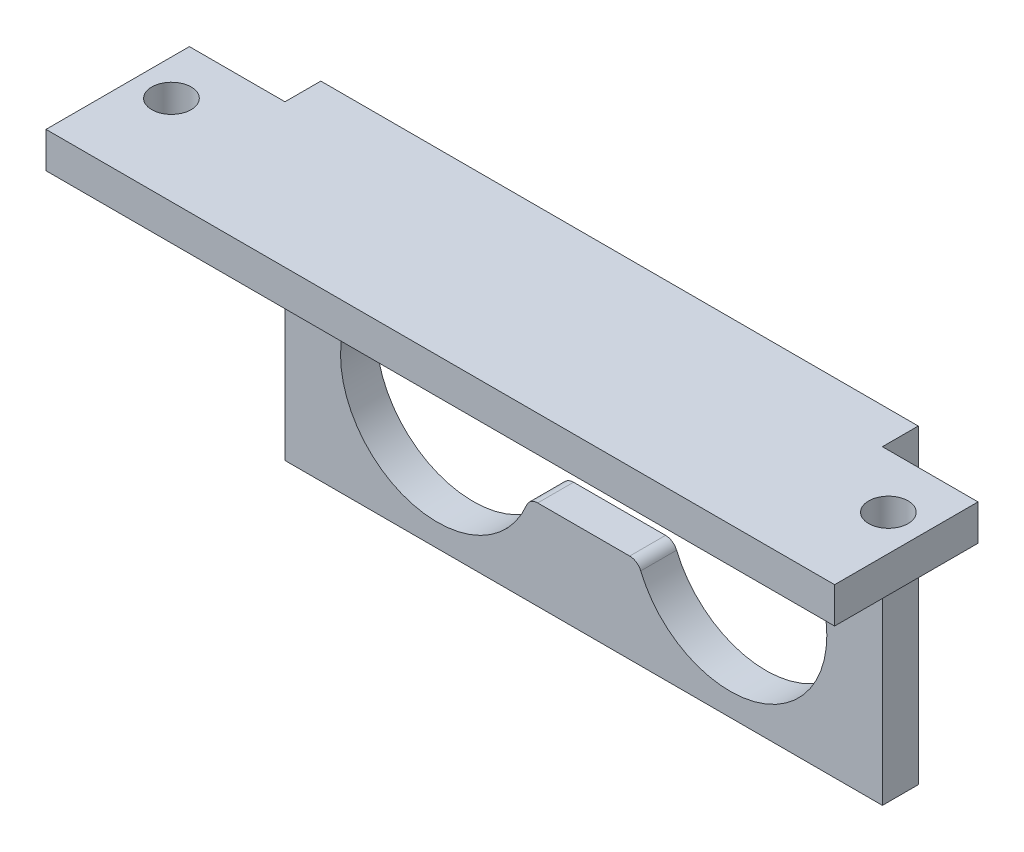
SolidWorks part; units mm, degrees
ref_plane "前视基准面" through (0, 0, 0) normal (0, 0, 1) x (1, 0, 0)
ref_plane "上视基准面" through (0, 0, 0) normal (0, 1, 0) x (1, 0, 0)
ref_plane "右视基准面" through (0, 0, 0) normal (1, 0, 0) x (0, 0, -1)
sketch "草图1" plane through (0, 0, 0) normal (0, 0, 1) x (1, 0, 0)
  line L1 (25, -10) -> (-25, -10)
  line L2 (25, -10) -> (25, 10)
  line L3 (25, 10) -> (-25, 10)
  line L4 (-25, -10) -> (-25, 10)
  line L5 (25, -10) -> (-25, 10) construction
  line L6 (25, 10) -> (-25, -10) construction
  line L8 (-3.85, 2.5) -> (3.85, 2.5)
  line L9 (3.85, -2.5) -> (-3.85, -2.5)
  line L10 (3.25, 7.25) -> (-3.25, 7.25) construction
  line L11 (3.25, 5.5) -> (-3.25, 5.5)
  line L12 (3.25, 9) -> (-3.25, 9)
  arc A7 (4.7731, -3.1154) -> (4.7731, 3.1154) centre (12.25, 0) ccw
  arc A8 (-4.7731, 3.1154) -> (-4.7731, -3.1154) centre (-12.25, 0) ccw
  arc A9 (3.85, -2.5) -> (4.7731, -3.1154) centre (3.85, -3.5) cw
  arc A10 (3.85, 2.5) -> (4.7731, 3.1154) centre (3.85, 3.5) ccw
  arc A11 (-3.85, -2.5) -> (-4.7731, -3.1154) centre (-3.85, -3.5) ccw
  arc A12 (-3.85, 2.5) -> (-4.7731, 3.1154) centre (-3.85, 3.5) cw
  arc A13 (3.25, 5.5) -> (3.25, 9) centre (3.25, 7.25) ccw
  arc A14 (-3.25, 9) -> (-3.25, 5.5) centre (-3.25, 7.25) ccw
  point P0 (0, 0)
  point P22 (0, 7.25)
  dimension "D3" = 1
  dimension "D4" = 8.1
  dimension "D5" = 8.1
  dimension "D6" = 2.5
  dimension "D8" = 12.25
  dimension "D9" = 12.25
  dimension "D12" = 1.75
  dimension "D1" = 20
  dimension "D2" = 50
  dimension "D7" = 2.5
  dimension "D10" = 7.25
  dimension "D11" = 6.5
  dimension "D13" = 3.25
extrude "凸台-拉伸1" add sketch "草图1" along normal blind 3
sketch "草图2" plane through (0, 10, 0) normal (0, 1, 0) x (1, 0, 0)
  line L1 (-25, 0) -> (25, 0)
  line L2 (-25, 0) -> (-25, -15)
  line L3 (-25, -15) -> (25, -15)
  line L4 (25, 0) -> (25, -15)
  dimension "D1" = 15
extrude "凸台-拉伸2" add sketch "草图2" along normal blind 6
sketch "草图5" plane through (0, 10, 0) normal (0, -1, 0) x (1, 0, 0)
  line L1 (25, 3) -> (-25, 3)
  line L2 (25, 3) -> (25, 15)
  line L3 (25, 15) -> (-25, 15)
  line L4 (-25, 3) -> (-25, 15)
extrude "切除-拉伸2" cut sketch "草图5" against normal blind 3
sketch "草图6" plane through (0, 16, 0) normal (0, 1, 0) x (1, 0, 0)
  line L1 (25, -15) -> (33, -15)
  line L2 (25, -15) -> (25, -3)
  line L3 (25, -3) -> (33, -3)
  line L4 (33, -15) -> (33, -3)
  line L5 (-25, -15) -> (-33, -15)
  line L6 (-25, -15) -> (-25, -3)
  line L7 (-25, -3) -> (-33, -3)
  line L8 (-33, -15) -> (-33, -3)
  circle A0 centre (30, -7.5) radius 1.65
  circle A1 centre (-30, -7.5) radius 1.65
  dimension "D5" = 3.3
  dimension "D6" = 3.3
  dimension "D1" = 12
  dimension "D2" = 8
  dimension "D3" = 8
  dimension "D4" = 12
extrude "凸台-拉伸3" add sketch "草图6" against normal blind 3
sketch "草图7" plane through (0, 0, 0) normal (0, 1, 0) x (1, 0, 0)
